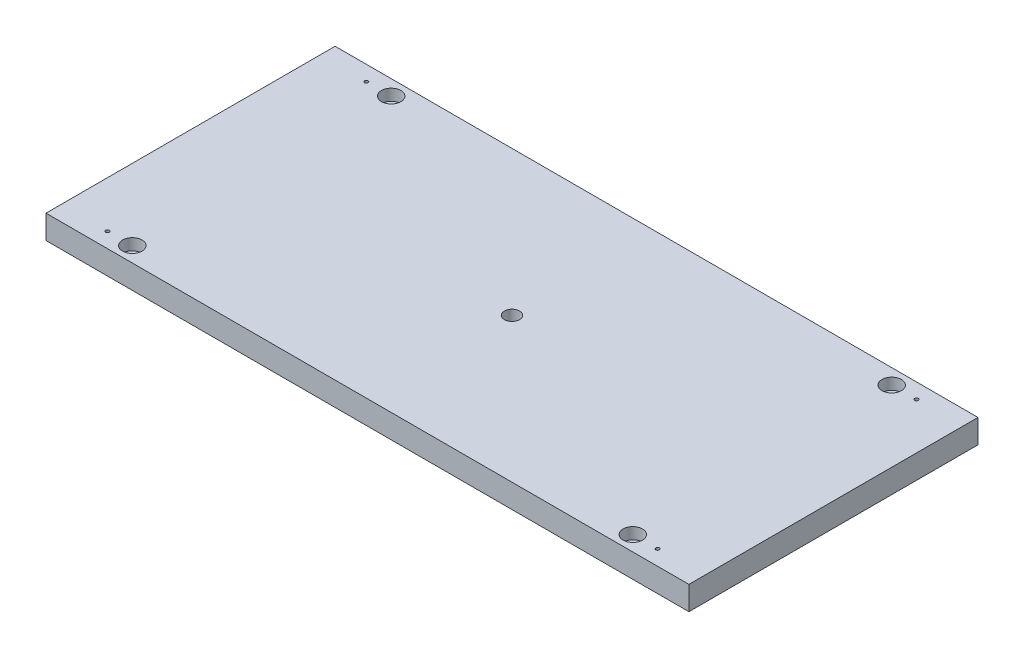
SolidWorks part; units mm, degrees
material "1.0725 (15SMn13)"
ref_plane "Płaszczyzna przednia" through (0, 0, 0) normal (0, 0, 1) x (1, 0, 0)
ref_plane "Płaszczyzna górna" through (0, 0, 0) normal (0, 1, 0) x (1, 0, 0)
ref_plane "Płaszczyzna prawa" through (0, 0, 0) normal (1, 0, 0) x (0, 0, -1)
sketch "Szkic1" plane through (0, 0, 0) normal (0, 1, 0) x (1, 0, 0)
  line L1 (0, 0) -> (596, 0)
  line L2 (0, 0) -> (0, 268)
  line L3 (0, 268) -> (596, 268)
  line L4 (596, 0) -> (596, 268)
  dimension "D1" = 596
  dimension "D2" = 268
extrude "Dodanie-wyciągnięcie1" add sketch "Szkic1" along normal blind 22
sketch "Szkic2" plane through (0, 22, 0) normal (0, 1, 0) x (1, 0, 0)
  line L0 (298, 268) -> (298, 0) construction
  line L1 (596, 268) -> (0, 268) construction
  line L2 (0, 0) -> (596, 0) construction
  line L3 (530, 254) -> (66, 254)
  line L4 (66, 14) -> (530, 14)
  line L5 (66, 254) -> (66, 14)
  line L6 (530, 254) -> (530, 14)
  point P10 (298, 254)
  point P12 (298, 14)
  dimension "D1" = 14
  dimension "D2" = 240
  dimension "D3" = 464
hole_wizard "Pogłębienie walcowe pod M10 Wkręt z łbem walcowym z gniazdem sześciokątnym1" positions "Szkic 3D1" profile "Szkic3" counterbore size "M10" standard "ISO" end condition through all
sketch3d "Szkic 3D1"
  point P0 (66, 22, -254)
  point P3 (66, 22, -14)
  point P6 (530, 22, -14)
  point P9 (530, 22, -254)
sketch "Szkic3" plane through (66, 22, -254) normal (1, 0, 0) x (0, 0, 1)
  line L0 (0, 0) -> (0, 22)
  line L1 (0, 22) -> (5.5, 22)
  line L3 (5.5, 22) -> (5.5, 10.6)
  line L4 (5.5, 10.6) -> (9, 10.6)
  line L5 (9, 10.6) -> (9, 0)
  line L7 (9, 0) -> (0, 0)
  line L11 (0, -6.35) -> (0, 107.95) construction
  dimension "Średnica otworu na wylot" = 11
  dimension "Głębokość otworu na wylot" = 22
  dimension "Średnica pogłębienia walcowego" = 18
  dimension "Głębokość pogłębienia walcowego" = 10.6
sketch "Szkic4" plane through (0, 22, 0) normal (0, 1, 0) x (1, 0, 0)
  line L0 (553, 254) -> (43, 254) construction
  line L1 (553, 14) -> (43, 14) construction
  line L2 (43, 14) -> (43, 254) construction
  line L3 (298, 268) -> (298, 0) construction
  line L4 (553, 14) -> (553, 254) construction
  point P11 (298, 14)
  point P12 (298, 254)
  dimension "D1" = 510
hole_wizard "Otwór gwintowany M41" positions "Szkic 3D2" profile "Szkic5" tap size "M4" standard "ISO"
sketch3d "Szkic 3D2"
  point P0 (43, 22, -14)
  point P3 (43, 22, -254)
  point P6 (553, 22, -254)
  point P9 (553, 22, -14)
sketch "Szkic5" plane through (43, 22, -14) normal (1, 0, 0) x (0, 0, 1)
  line L0 (0, 0) -> (0, 12.4914)
  line L1 (0, 12.4914) -> (1.65, 11.5)
  line L2 (1.65, 11.5) -> (1.65, 0)
  line L5 (1.65, 0) -> (0, 0)
  line L10 (0, 12.4914) -> (-1.65, 11.5) construction
  line L11 (0, -6.35) -> (0, 107.95) construction
  dimension "Średnica wiertła gwintu" = 3.3
  dimension "Głębokość otworu gwintowanego" = 11.5
  dimension "Kąt wiertła" = 118
cosmetic thread "Gwint otworu1" parameters "D1"=8, "D2"=4
cosmetic thread "Gwint otworu2" parameters "D1"=8, "D2"=4
cosmetic thread "Gwint otworu3" parameters "D1"=8, "D2"=4
cosmetic thread "Gwint otworu4" parameters "D1"=8, "D2"=4
sketch "Szkic6" plane through (0, 22, 0) normal (0, 1, 0) x (1, 0, 0)
  line L0 (298, 268) -> (298, 0) construction
  line L1 (596, 268) -> (0, 268) construction
  line L2 (0, 0) -> (596, 0) construction
  circle A0 centre (298, 134) radius 20
  circle A1 centre (298, 134) radius 22.5
  circle A2 centre (298, 134) radius 15
  dimension "D1" = 30
hole_wizard "Otwór gwintowany M161" positions "Szkic 3D3" profile "Szkic7" tap size "M16" standard "ISO" end condition through all
sketch3d "Szkic 3D3"
  point P0 (298, 22, -134)
sketch "Szkic7" plane through (298, 22, -134) normal (1, 0, 0) x (0, 0, 1)
  line L0 (0, 0) -> (0, 22)
  line L1 (0, 22) -> (7, 22)
  line L2 (7, 22) -> (7, 0)
  line L5 (7, 0) -> (0, 0)
  line L11 (0, -6.35) -> (0, 107.95) construction
  dimension "Średnica otworu gwintowanego na wylot" = 14
  dimension "Głębokość otworu gwintowanego na wylot" = 22
cosmetic thread "Gwint otworu5" parameters "D2"=16
extrude "Wytnij-wyciągnięcie4" [suppressed] cut sketch "Szkic6" against normal blind 5 contours A2 L0 | L0 A2 | A0
